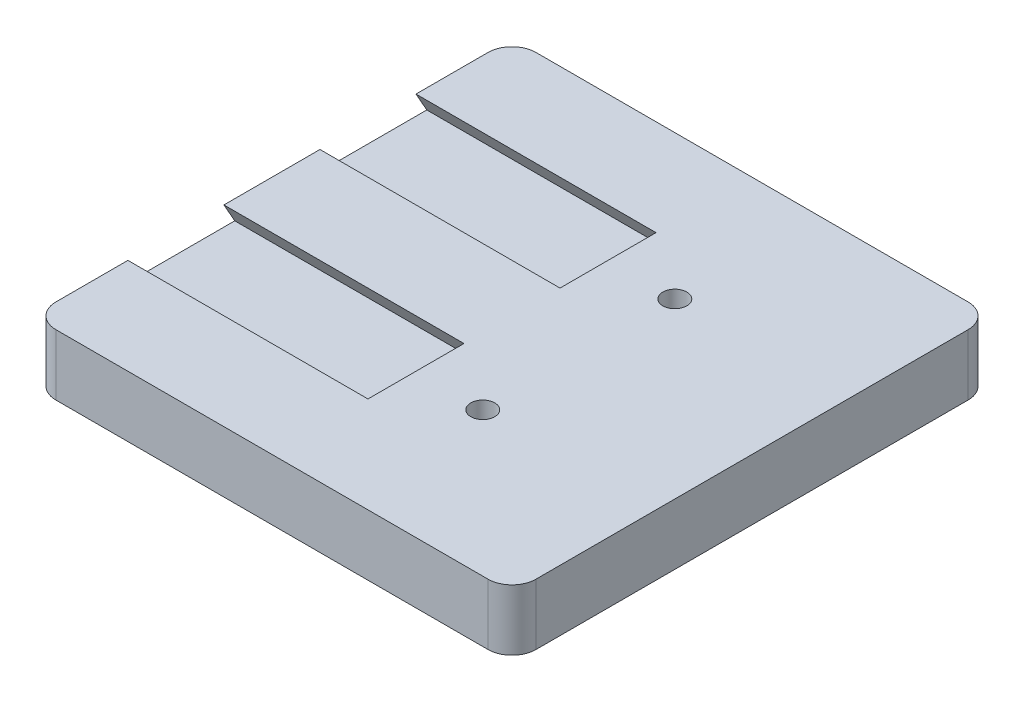
SolidWorks part; units mm, degrees
material "Liga 1060"
ref_plane "Plano frontal" through (0, 0, 0) normal (0, 0, 1) x (1, 0, 0)
ref_plane "Plano superior" through (0, 0, 0) normal (0, 1, 0) x (1, 0, 0)
ref_plane "Plano direito" through (0, 0, 0) normal (1, 0, 0) x (0, 0, -1)
sketch "Esboço2" plane through (0, 0, 0) normal (0, 1, 0) x (1, 0, 0)
  line L1 (50, -50) -> (-50, -50)
  line L2 (50, -50) -> (50, 50)
  line L3 (50, 50) -> (-50, 50)
  line L4 (-50, -50) -> (-50, 50)
  line L5 (50, -50) -> (-50, 50) construction
  line L6 (50, 50) -> (-50, -50) construction
  point P0 (0, 0)
  dimension "D1" = 100
  dimension "D2" = 100
extrude "Ressalto-extrusão1" add sketch "Esboço2" along normal blind 12.7
sketch "Esboço4" plane through (0, 0, 0) normal (1, 0, 0) x (0, 0, -1)
  line L0 (-30, 12.7) -> (-10, 12.7)
  line L1 (-50, 12.7) -> (50, 12.7) construction
  line L2 (-10, 12.7) -> (-7.75, 8.7)
  line L3 (-7.75, 8.7) -> (-32.25, 8.7)
  line L4 (-32.25, 8.7) -> (-30, 12.7)
  dimension "D1" = 20
  dimension "D2" = 24.5
  dimension "D3" = 10
  dimension "D4" = 4
extrude "Corte-extrusão1" cut sketch "Esboço4" against normal through all
mirror "Espelhar1" about plane through (0, 0, 0) normal (0, 0, 1) of "Corte-extrusão1"
sketch "Esboço7" plane through (0, 0, 0) normal (0, -1, 0) x (1, 0, 0)
  circle A0 centre (0, 0) radius 2.95
  dimension "D1" = 5.9
extrude "Corte-extrusão3" cut sketch "Esboço7" against normal blind 3.5
sketch "Esboço8" plane through (0, 0, 0) normal (0, -1, 0) x (-1, 0, 0)
  line L0 (0, -2.95) -> (0, -2.78) construction
  line L1 (0, -2.78) -> (-0.338, -2.9306)
  line L2 (0, -2.78) -> (0.338, -2.9306)
  line L3 (0.338, -2.9306) -> (-0.338, -2.9306) construction
  line L4 (0.338, -2.9306) -> (0.338, -2.9817)
  line L5 (0.338, -2.9817) -> (-0.338, -2.9817)
  line L6 (-0.338, -2.9817) -> (-0.338, -2.9306)
  circle A0 centre (0, 0) radius 2.95 construction
  circle A1 centre (0, 0) radius 2.95 construction
  dimension "D1" = 0.37
  dimension "D2" = 0.17
extrude "Ressalto-extrusão4" add sketch "Esboço8" against normal up to surface (3.5 mm away) up to face at (0, 3.5, -2.95)
pattern_circular "PadrãoCircular1" count 26 over 360 about axis through (0, 0, 0) along (0, 1, 0) of "Ressalto-extrusão4"
fillet "Filete2" radius 5 4 edges at (-50, 6.35, -50) (50, 6.35, -50) (50, 6.35, 50) (-50, 6.35, 50)
sketch "Esboço9" plane through (0, 0, 0) normal (0, -1, 0) x (1, 0, 0)
  line L0 (13.9125, -50) -> (13.9125, 50) construction
  line L1 (45, -50) -> (-45, -50) construction
  line L2 (-45, 50) -> (45, 50) construction
  circle A0 centre (13.9125, 20) radius 4
  circle A1 centre (13.9125, -20) radius 4
  dimension "D2" = 8
  dimension "D1" = 13.9125
  dimension "D3" = 30
  dimension "D4" = 30
hole_wizard "Furo roscado de M61" positions "Esboço10" profile "Esboço11" tap size "M6" standard "ISO" end condition through all
sketch "Esboço10" plane through (0, 0, 0) normal (0, -1, 0) x (-1, 0, 0)
  point P0 (-13.9125, -20)
  point P3 (-13.9125, 20)
sketch "Esboço11" plane through (13.9125, 0, 20) normal (1, 0, 0) x (0, 0, -1)
  line L0 (0, 0) -> (0, 12.7)
  line L1 (0, 12.7) -> (2.5, 12.7)
  line L2 (2.5, 12.7) -> (2.5, 0)
  line L5 (2.5, 0) -> (0, 0)
  line L11 (0, -6.35) -> (0, 107.95) construction
  dimension "Thru Tap Drill Dia." = 5
  dimension "Thru Tap Drill Depth" = 12.7
cosmetic thread "Rosca de furo1" parameters "D2"=6
cosmetic thread "Rosca de furo2" parameters "D2"=6
